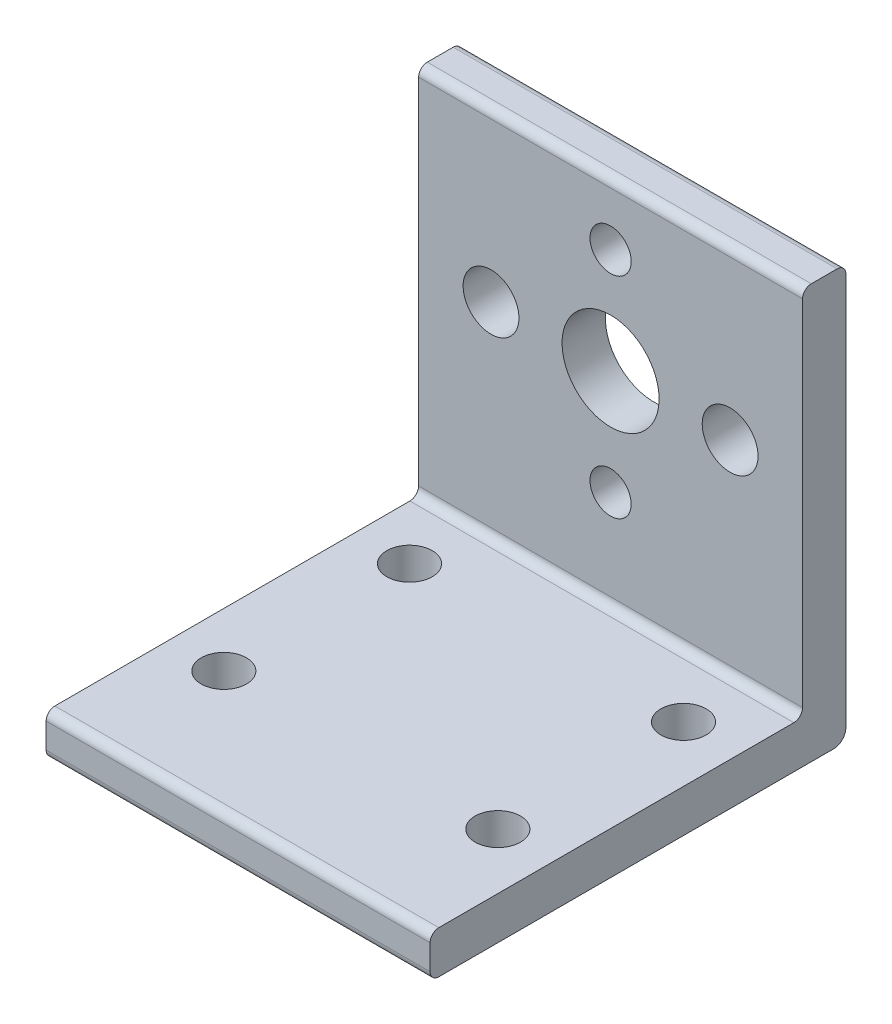
SolidWorks part; units mm, degrees
material "6061-T6 (SS)"
ref_plane "Front Plane" through (0, 0, 0) normal (0, 0, 1) x (1, 0, 0)
ref_plane "Top Plane" through (0, 0, 0) normal (0, 1, 0) x (1, 0, 0)
ref_plane "Right Plane" through (0, 0, 0) normal (1, 0, 0) x (0, 0, -1)
sketch "Sketch1" plane through (0, 0, 0) normal (1, 0, 0) x (0, 0, -1)
  line L0 (0, 0) -> (0, -30.1244)
  line L1 (0, -30.1244) -> (-30.2514, -30.1244)
  line L2 (-30.2514, -30.1244) -> (-30.2514, -27.0256)
  line L3 (-30.2514, -27.0256) -> (-3.1496, -27.0256)
  line L4 (-3.1496, -27.0256) -> (-3.1496, 0)
  line L5 (-3.1496, 0) -> (0, 0)
  dimension "D1" = 30.2514
  dimension "D2" = 30.1244
  dimension "D3" = 3.1496
  dimension "D4" = 3.0988
extrude "Boss-Extrude1" add sketch "Sketch1" along normal blind 27.94
sketch "Sketch2" plane through (0, 0, 0) normal (0, 0, 1) x (1, 0, 0)
  line L0 (13.97, -4.5212) -> (13.97, -19.812) construction
  line L1 (27.94, -30.1244) -> (0, -30.1244) construction
  line L2 (27.94, 0) -> (0, 0) construction
  line L3 (5.2705, -12.1666) -> (22.6695, -12.1666) construction
  line L4 (27.94, -27.0256) -> (0, -27.0256) construction
  line L6 (0, -12.1666) -> (27.94, -12.1666) construction
  line L9 (0, 0) -> (0, -27.0256) construction
  line L10 (27.94, 0) -> (27.94, -27.0256) construction
  circle A0 centre (13.97, -12.1666) radius 3.5306
  circle A1 centre (13.97, -4.5212) radius 1.4986
  circle A2 centre (5.2705, -12.1666) radius 2.032
  circle A3 centre (22.6695, -12.1666) radius 2.032
  circle A4 centre (13.97, -19.812) radius 1.4986
  point P0 (13.97, -12.1666)
  dimension "D1" = 7.0612
  dimension "D2" = 2.9972
  dimension "D3" = 12.1666
  dimension "D7" = 4.064
  dimension "D8" = 27.94
  dimension "D4" = 17.399
  dimension "D5" = 15.2908
  dimension "D6" = 30.1244
  dimension "D9" = 3.0988
extrude "Motor_Mount_holes" cut sketch "Sketch2" along normal through all
sketch "Sketch3" plane through (0, -30.1244, 0) normal (0, 1, 0) x (1, 0, 0)
  line L0 (13.97, -3.1496) -> (13.97, -30.2514) construction
  line L1 (27.94, -3.1496) -> (0, -3.1496) construction
  line L2 (27.94, -30.2514) -> (0, -30.2514) construction
  line L3 (27.94, 0) -> (0, 0) construction
  line L4 (27.94, -30.2514) -> (27.94, 0) construction
  line L5 (0, -14.5669) -> (28.2702, -14.5669) construction
  line L6 (27.94, 0) -> (0, 0) construction
  line L7 (27.94, -3.1496) -> (0, -3.1496) construction
  line L8 (0, -3.1496) -> (0, -30.2514) construction
  line L9 (27.94, -3.1496) -> (27.94, -30.2514) construction
  circle A4 centre (3.937, -7.747) radius 1.651
  circle A5 centre (23.876, -7.747) radius 1.651
  circle A6 centre (3.937, -21.2598) radius 1.651
  circle A7 centre (23.876, -21.2598) radius 1.651
  dimension "D1" = 3.302
  dimension "D2" = 7.747
  dimension "D3" = 4.064
  dimension "D4" = 21.2598
  dimension "D5" = 4.064
  dimension "D6" = 7.747
  dimension "D7" = 24.003
  dimension "D8" = 21.2598
  dimension "D9" = 24.003
  dimension "D10" = 3.1496
  dimension "D11" = 27.94
  dimension "D12" = 30.2514
extrude "Plate_Mount_Holes" cut sketch "Sketch3" along normal through all
fillet "Fillet1" radius 0.635 1 edges at (13.97, -27.0256, 3.1496)
fillet "Fillet2" radius 0.889 1 edges at (13.97, -30.1244, 0)
fillet "Fillet3" radius 0.635 4 edges at (13.97, -30.1244, 30.2514) (13.97, -27.0256, 30.2514) (13.97, 0, 0) (13.97, 0, 3.1496)
